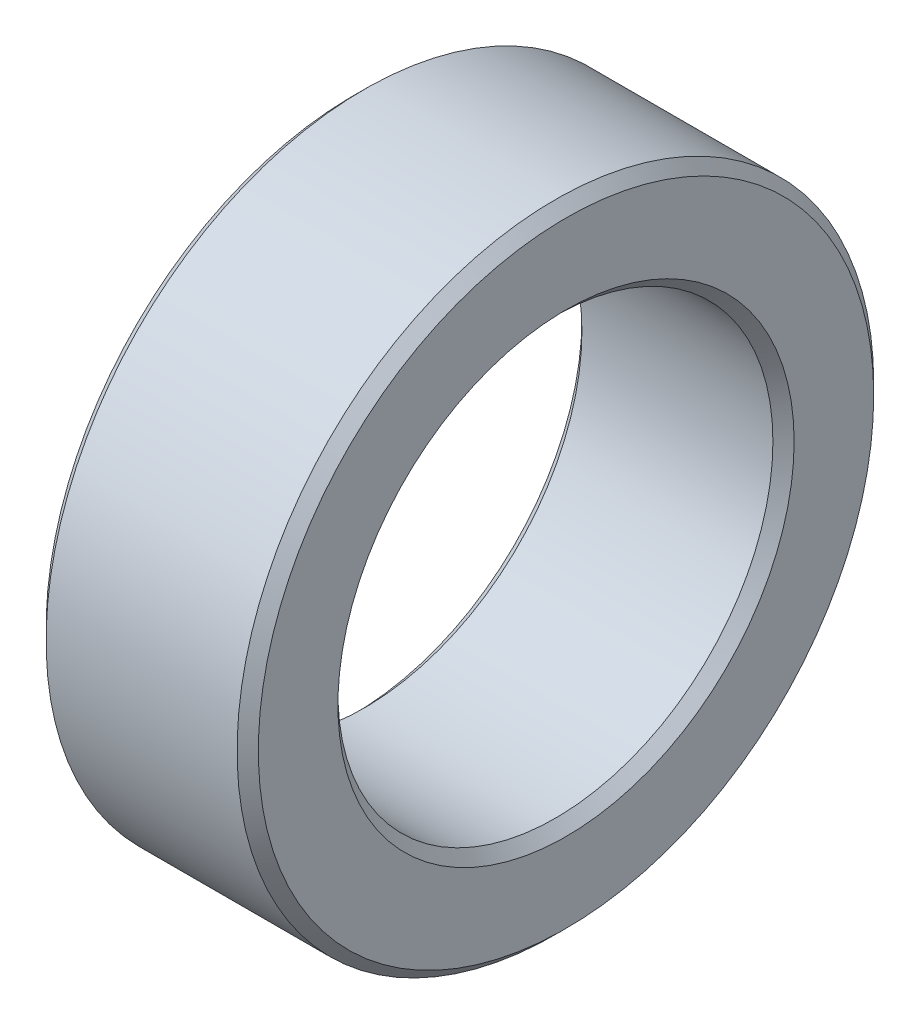
SolidWorks part; units mm, degrees
material "黄铜"
ref_plane "前视基准面" through (0, 0, 0) normal (1, 0, 0) x (0, 1, 0)
ref_plane "上视基准面" through (0, 0, 0) normal (0, 0, 1) x (0, 1, 0)
ref_plane "右视基准面" through (0, 0, 0) normal (0, 1, 0) x (-1, 0, 0)
other "Configuration Table"
sketch "草图1" plane through (0, 0, 0) normal (1, 0, 0) x (0, 1, 0)
  circle A0 centre (0, 0) radius 3
  circle A1 centre (0, 0) radius 2.05
  dimension "D1" = 6
  dimension "D2" = 4.1
extrude "凸台-拉伸1" add sketch "草图1" along normal blind 2
chamfer "倒角1" distance 0.1 angle 45 4 edges at (2, 0, -2.05) (0, 0, -2.05) (0, 0, -3) (2, 0, -3)
